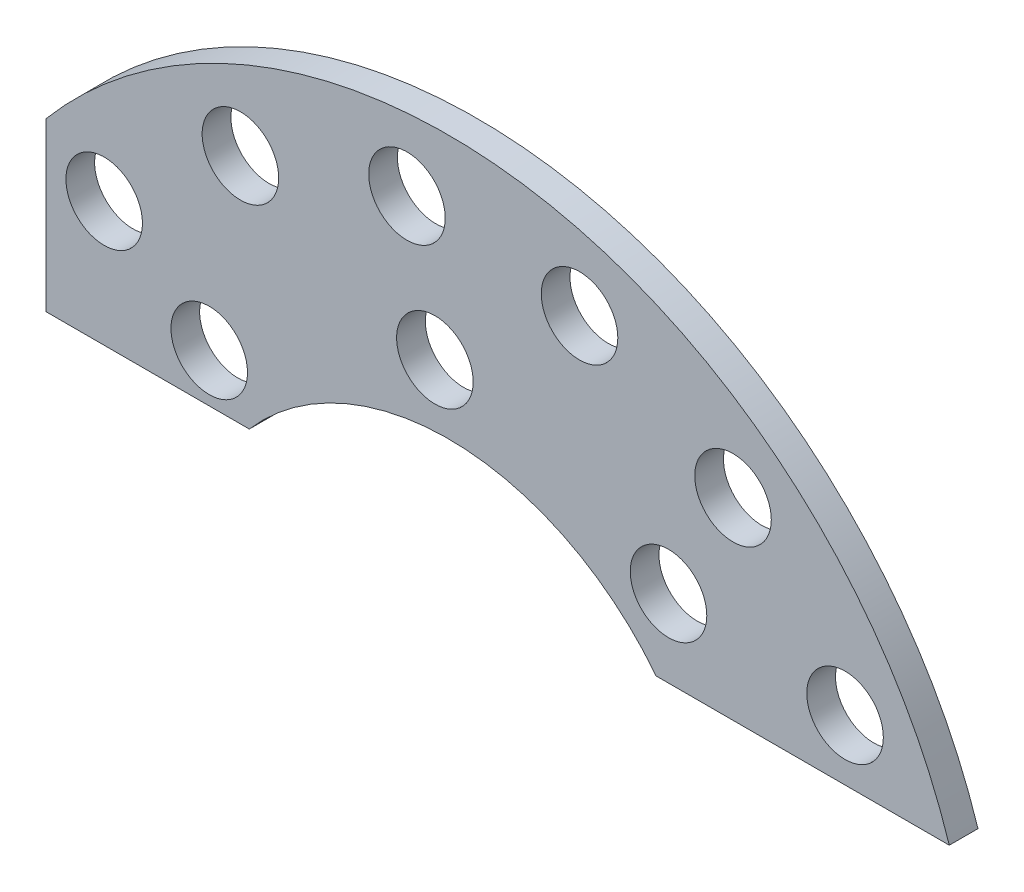
SolidWorks part; units mm, degrees
ref_plane "Front Plane" through (0, 0, 0) normal (0, 0, 1) x (1, 0, 0)
ref_plane "Top Plane" through (0, 0, 0) normal (0, 1, 0) x (1, 0, 0)
ref_plane "Right Plane" through (0, 0, 0) normal (1, 0, 0) x (0, 0, -1)
sketch "Sketch2" plane through (0, 0, 29.6705) normal (0, 0, 1) x (1, 0, 0)
  line L0 (-71.5138, 33.0495) -> (-71.5138, 15.5822)
  line L1 (-71.5138, 15.5822) -> (-50.2684, 15.5822)
  line L2 (-7.7546, 14.4953) -> (22.8855, 14.4953)
  arc A0 (-7.7546, 14.4953) -> (-50.2684, 15.5822) centre (-29.4571, -2.3939) ccw
  arc A1 (22.8855, 14.4953) -> (-71.5138, 33.0495) centre (-29.4571, -2.3939) ccw
  arc A2 (14.9388, 14.4953) -> (-71.5138, 19.6851) centre (-29.4571, -2.3939) ccw
  circle A3 centre (-65.4335, 28.6214) radius 4
  circle A4 centre (-51.1953, 39.8399) radius 4
  circle A5 centre (-33.7914, 44.9079) radius 4
  circle A6 centre (-15.7562, 43.0872) radius 4
  circle A7 centre (0.2837, 34.643) radius 4
  circle A8 centre (11.9924, 20.805) radius 4
  circle A9 centre (-30.8714, 31.5472) radius 4
  circle A10 centre (-6.4571, 22.6061) radius 4
  circle A11 centre (-54.4571, 20.6061) radius 4
  point P24 (-29.4571, -2.3939)
  circle M13 centre (-6.4571, 22.6061) radius 4
  circle M14 centre (-30.8714, 31.5472) radius 4
  circle M15 centre (-54.4571, 20.6061) radius 4
  circle M17 centre (-29.4571, -2.3939) radius 40
  dimension "D1" = 110
  dimension "D2" = 55
  dimension "D3" = 95
  dimension "D4" = 8
  dimension "D5" = 6
extrude "Boss-Extrude1" add sketch "Sketch2" along normal blind 3 contours A0 L2 L1 M17 M13 M15 M14 | A8 A2 A7 A6 A5 A4 A3 L0 L1 L2 M17 | A8 A2 L2 A1 L0 A3 A4 A5 A6 A7
